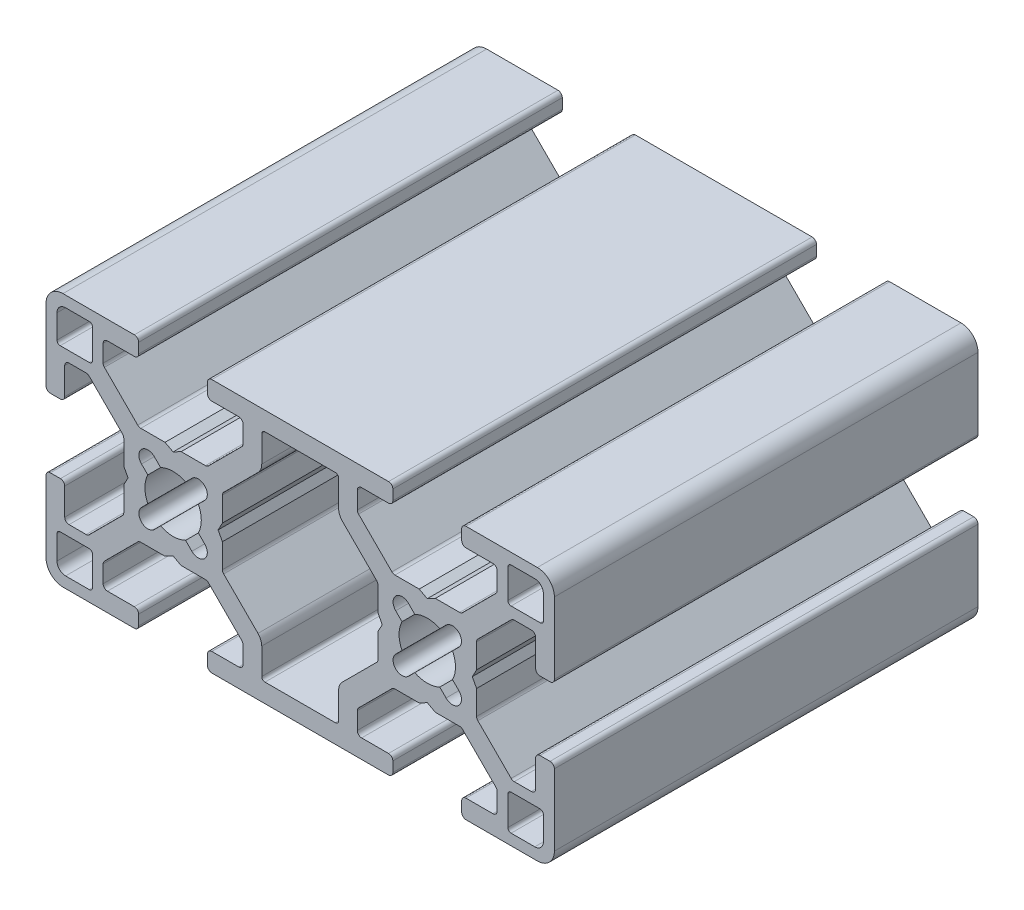
SolidWorks part; units mm, degrees
material "6105-T5 Aluminum"
ref_plane "Front Plane" through (0, 0, 0) normal (0, 0, 1) x (1, 0, 0)
ref_plane "Top Plane" through (0, 0, 0) normal (0, 1, 0) x (1, 0, 0)
ref_plane "Right Plane" through (0, 0, 0) normal (1, 0, 0) x (0, 0, -1)
sketch "Sketch1" plane through (0, 0, 0) normal (0, 0, 1) x (1, 0, 0)
  line L0 (12.7825, 3.7261) -> (13.5257, 2.983)
  line L1 (16.4743, 2.983) -> (17.2175, 3.7261)
  line L2 (18.7261, 2.2175) -> (17.983, 1.4743)
  line L3 (17.983, -1.4743) -> (18.7261, -2.2175)
  line L4 (17.2175, -3.7261) -> (16.4743, -2.983)
  line L5 (13.5257, -2.983) -> (12.7825, -3.7261)
  line L6 (11.2739, -2.2175) -> (12.017, -1.4743)
  line L7 (12.017, 1.4743) -> (11.2739, 2.2175)
  line L8 (-28.7046, 9.8946) -> (-28.7046, 12.6886)
  line L9 (-27.6886, 13.7046) -> (-24.8946, 13.7046)
  line L10 (-24.5136, 13.3236) -> (-24.5136, 9.8946)
  line L11 (-24.8946, 9.5136) -> (-28.3236, 9.5136)
  line L12 (-24.8946, -13.7046) -> (-27.6886, -13.7046)
  line L13 (-28.7046, -12.6886) -> (-28.7046, -9.8946)
  line L14 (-28.3236, -9.5136) -> (-24.8946, -9.5136)
  line L15 (-24.5136, -9.8946) -> (-24.5136, -13.3236)
  line L16 (4.9816, 8.2224) -> (9.0292, 4.1748)
  line L17 (9.178, 3.8155) -> (9.178, 0.9525)
  line L18 (9.178, 0.9525) -> (9.686, 0)
  line L19 (9.686, 0) -> (9.178, -0.9525)
  line L20 (9.178, -0.9525) -> (9.178, -3.8155)
  line L21 (9.0292, -4.1748) -> (4.9816, -8.2224)
  line L22 (4.5352, -9.3) -> (4.5352, -12.4092)
  line L23 (4.1542, -12.7902) -> (-4.1542, -12.7902)
  line L24 (-4.5352, -12.4092) -> (-4.5352, -9.3)
  line L25 (-4.9816, -8.2224) -> (-9.0292, -4.1748)
  line L26 (-9.178, -3.8155) -> (-9.178, -0.9525)
  line L27 (-9.178, -0.9525) -> (-9.686, 0)
  line L28 (-9.686, 0) -> (-9.178, 0.9525)
  line L29 (-9.178, 0.9525) -> (-9.178, 3.8155)
  line L30 (-9.0292, 4.1748) -> (-4.9816, 8.2224)
  line L31 (-4.5352, 9.3) -> (-4.5352, 12.4092)
  line L32 (-4.1542, 12.7902) -> (4.1542, 12.7902)
  line L33 (4.5352, 12.4092) -> (4.5352, 9.3)
  line L34 (-18.7261, -2.2175) -> (-17.983, -1.4743)
  line L35 (-17.983, 1.4743) -> (-18.7261, 2.2175)
  line L36 (-17.2175, 3.7261) -> (-16.4743, 2.983)
  line L37 (-13.5257, 2.983) -> (-12.7825, 3.7261)
  line L38 (-11.2739, 2.2175) -> (-12.017, 1.4743)
  line L39 (-12.017, -1.4743) -> (-11.2739, -2.2175)
  line L40 (-12.7825, -3.7261) -> (-13.5257, -2.983)
  line L41 (-16.4743, -2.983) -> (-17.2175, -3.7261)
  line L42 (24.8946, 13.7046) -> (27.6886, 13.7046)
  line L43 (28.7046, 12.6886) -> (28.7046, 9.8946)
  line L44 (28.3236, 9.5136) -> (24.8946, 9.5136)
  line L45 (24.5136, 9.8946) -> (24.5136, 13.3236)
  line L46 (24.5136, -13.3236) -> (24.5136, -9.8946)
  line L47 (24.8946, -9.5136) -> (28.3236, -9.5136)
  line L48 (28.7046, -9.8946) -> (28.7046, -12.6886)
  line L49 (27.6886, -13.7046) -> (24.8946, -13.7046)
  line L50 (-10.428, -15) -> (10.428, -15)
  line L51 (10.936, -14.492) -> (10.936, -13.2982)
  line L52 (10.428, -12.7902) -> (7.253, -12.7902)
  line L53 (6.745, -12.2822) -> (6.745, -10.2615)
  line L54 (6.8938, -9.9023) -> (10.8252, -5.9708)
  line L55 (11.1845, -5.822) -> (14.0475, -5.822)
  line L56 (14.0475, -5.822) -> (15, -5.314)
  line L57 (15, -5.314) -> (15.9525, -5.822)
  line L58 (15.9525, -5.822) -> (18.8155, -5.822)
  line L59 (19.1748, -5.9708) -> (23.1062, -9.9023)
  line L60 (23.255, -10.2615) -> (23.255, -12.2822)
  line L61 (22.747, -12.7902) -> (19.572, -12.7902)
  line L62 (19.064, -13.2982) -> (19.064, -14.492)
  line L63 (19.572, -15) -> (27.9934, -15)
  line L64 (30, -12.9934) -> (30, -4.572)
  line L65 (29.492, -4.064) -> (28.2982, -4.064)
  line L66 (27.7902, -4.572) -> (27.7902, -7.747)
  line L67 (27.2822, -8.255) -> (25.2615, -8.255)
  line L68 (24.9023, -8.1062) -> (20.9708, -4.1748)
  line L69 (20.822, -3.8155) -> (20.822, -0.9525)
  line L70 (20.822, -0.9525) -> (20.314, 0)
  line L71 (20.314, 0) -> (20.822, 0.9525)
  line L72 (20.822, 0.9525) -> (20.822, 3.8155)
  line L73 (20.9708, 4.1748) -> (24.9023, 8.1062)
  line L74 (25.2615, 8.255) -> (27.2822, 8.255)
  line L75 (27.7902, 7.747) -> (27.7902, 4.572)
  line L76 (28.2982, 4.064) -> (29.492, 4.064)
  line L77 (30, 4.572) -> (30, 12.9934)
  line L78 (27.9934, 15) -> (19.572, 15)
  line L79 (19.064, 14.492) -> (19.064, 13.2982)
  line L80 (19.572, 12.7902) -> (22.747, 12.7902)
  line L81 (23.255, 12.2822) -> (23.255, 10.2615)
  line L82 (23.1062, 9.9023) -> (19.1748, 5.9708)
  line L83 (18.8155, 5.822) -> (15.9525, 5.822)
  line L84 (15.9525, 5.822) -> (15, 5.314)
  line L85 (15, 5.314) -> (14.0475, 5.822)
  line L86 (14.0475, 5.822) -> (11.1845, 5.822)
  line L87 (10.8252, 5.9708) -> (6.8938, 9.9023)
  line L88 (6.745, 10.2615) -> (6.745, 12.2822)
  line L89 (7.253, 12.7902) -> (10.428, 12.7902)
  line L90 (10.936, 13.2982) -> (10.936, 14.492)
  line L91 (10.428, 15) -> (-10.428, 15)
  line L92 (-10.936, 14.492) -> (-10.936, 13.2982)
  line L93 (-10.428, 12.7902) -> (-7.253, 12.7902)
  line L94 (-6.745, 12.2822) -> (-6.745, 10.2615)
  line L95 (-6.8938, 9.9023) -> (-10.8252, 5.9708)
  line L96 (-11.1845, 5.822) -> (-14.0475, 5.822)
  line L97 (-14.0475, 5.822) -> (-15, 5.314)
  line L98 (-15, 5.314) -> (-15.9525, 5.822)
  line L99 (-15.9525, 5.822) -> (-18.8155, 5.822)
  line L100 (-19.1748, 5.9708) -> (-23.1062, 9.9023)
  line L101 (-23.255, 10.2615) -> (-23.255, 12.2822)
  line L102 (-22.747, 12.7902) -> (-19.572, 12.7902)
  line L103 (-19.064, 13.2982) -> (-19.064, 14.492)
  line L104 (-19.572, 15) -> (-27.9934, 15)
  line L105 (-30, 12.9934) -> (-30, 4.572)
  line L106 (-29.492, 4.064) -> (-28.2982, 4.064)
  line L107 (-27.7902, 4.572) -> (-27.7902, 7.747)
  line L108 (-27.2822, 8.255) -> (-25.2615, 8.255)
  line L109 (-24.9023, 8.1062) -> (-20.9708, 4.1748)
  line L110 (-20.822, 3.8155) -> (-20.822, 0.9525)
  line L111 (-20.822, 0.9525) -> (-20.314, 0)
  line L112 (-20.314, 0) -> (-20.822, -0.9525)
  line L113 (-20.822, -0.9525) -> (-20.822, -3.8155)
  line L114 (-20.9708, -4.1748) -> (-24.9023, -8.1062)
  line L115 (-25.2615, -8.255) -> (-27.2822, -8.255)
  line L116 (-27.7902, -7.747) -> (-27.7902, -4.572)
  line L117 (-28.2982, -4.064) -> (-29.492, -4.064)
  line L118 (-30, -4.572) -> (-30, -12.9934)
  line L119 (-27.9934, -15) -> (-19.572, -15)
  line L120 (-19.064, -14.492) -> (-19.064, -13.2982)
  line L121 (-19.572, -12.7902) -> (-22.747, -12.7902)
  line L122 (-23.255, -12.2822) -> (-23.255, -10.2615)
  line L123 (-23.1062, -9.9023) -> (-19.1748, -5.9708)
  line L124 (-18.8155, -5.822) -> (-15.9525, -5.822)
  line L125 (-15.9525, -5.822) -> (-15, -5.314)
  line L126 (-15, -5.314) -> (-14.0475, -5.822)
  line L127 (-14.0475, -5.822) -> (-11.1845, -5.822)
  line L128 (-10.8252, -5.9708) -> (-6.8938, -9.9023)
  line L129 (-6.745, -10.2615) -> (-6.745, -12.2822)
  line L130 (-7.253, -12.7902) -> (-10.428, -12.7902)
  line L131 (-10.936, -13.2982) -> (-10.936, -14.492)
  arc A0 (12.7825, 3.7261) -> (11.2739, 2.2175) centre (12.0282, 2.9718) ccw
  arc A1 (16.4743, 2.983) -> (13.5257, 2.983) centre (15, 0) ccw
  arc A2 (18.7261, 2.2175) -> (17.2175, 3.7261) centre (17.9718, 2.9718) ccw
  arc A3 (17.983, -1.4743) -> (17.983, 1.4743) centre (15, 0) ccw
  arc A4 (17.2175, -3.7261) -> (18.7261, -2.2175) centre (17.9718, -2.9718) ccw
  arc A5 (13.5257, -2.983) -> (16.4743, -2.983) centre (15, 0) ccw
  arc A6 (11.2739, -2.2175) -> (12.7825, -3.7261) centre (12.0282, -2.9718) ccw
  arc A7 (12.017, 1.4743) -> (12.017, -1.4743) centre (15, 0) ccw
  arc A8 (-28.7046, 9.8946) -> (-28.3236, 9.5136) centre (-28.3236, 9.8946) ccw
  arc A9 (-27.6886, 13.7046) -> (-28.7046, 12.6886) centre (-27.6886, 12.6886) ccw
  arc A10 (-24.5136, 13.3236) -> (-24.8946, 13.7046) centre (-24.8946, 13.3236) ccw
  arc A11 (-24.8946, 9.5136) -> (-24.5136, 9.8946) centre (-24.8946, 9.8946) ccw
  arc A12 (-24.8946, -13.7046) -> (-24.5136, -13.3236) centre (-24.8946, -13.3236) ccw
  arc A13 (-28.7046, -12.6886) -> (-27.6886, -13.7046) centre (-27.6886, -12.6886) ccw
  arc A14 (-28.3236, -9.5136) -> (-28.7046, -9.8946) centre (-28.3236, -9.8946) ccw
  arc A15 (-24.5136, -9.8946) -> (-24.8946, -9.5136) centre (-24.8946, -9.8946) ccw
  arc A16 (4.5352, 9.3) -> (4.9816, 8.2224) centre (6.0592, 9.3) ccw
  arc A17 (9.178, 3.8155) -> (9.0292, 4.1748) centre (8.67, 3.8155) ccw
  arc A18 (9.0292, -4.1748) -> (9.178, -3.8155) centre (8.67, -3.8155) ccw
  arc A19 (4.9816, -8.2224) -> (4.5352, -9.3) centre (6.0592, -9.3) ccw
  arc A20 (4.1542, -12.7902) -> (4.5352, -12.4092) centre (4.1542, -12.4092) ccw
  arc A21 (-4.5352, -12.4092) -> (-4.1542, -12.7902) centre (-4.1542, -12.4092) ccw
  arc A22 (-4.5352, -9.3) -> (-4.9816, -8.2224) centre (-6.0592, -9.3) ccw
  arc A23 (-9.178, -3.8155) -> (-9.0292, -4.1748) centre (-8.67, -3.8155) ccw
  arc A24 (-9.0292, 4.1748) -> (-9.178, 3.8155) centre (-8.67, 3.8155) ccw
  arc A25 (-4.9816, 8.2224) -> (-4.5352, 9.3) centre (-6.0592, 9.3) ccw
  arc A26 (-4.1542, 12.7902) -> (-4.5352, 12.4092) centre (-4.1542, 12.4092) ccw
  arc A27 (4.5352, 12.4092) -> (4.1542, 12.7902) centre (4.1542, 12.4092) ccw
  arc A28 (-18.7261, -2.2175) -> (-17.2175, -3.7261) centre (-17.9718, -2.9718) ccw
  arc A29 (-17.983, 1.4743) -> (-17.983, -1.4743) centre (-15, 0) ccw
  arc A30 (-17.2175, 3.7261) -> (-18.7261, 2.2175) centre (-17.9718, 2.9718) ccw
  arc A31 (-13.5257, 2.983) -> (-16.4743, 2.983) centre (-15, 0) ccw
  arc A32 (-11.2739, 2.2175) -> (-12.7825, 3.7261) centre (-12.0282, 2.9718) ccw
  arc A33 (-12.017, -1.4743) -> (-12.017, 1.4743) centre (-15, 0) ccw
  arc A34 (-12.7825, -3.7261) -> (-11.2739, -2.2175) centre (-12.0282, -2.9718) ccw
  arc A35 (-16.4743, -2.983) -> (-13.5257, -2.983) centre (-15, 0) ccw
  arc A36 (24.8946, 13.7046) -> (24.5136, 13.3236) centre (24.8946, 13.3236) ccw
  arc A37 (28.7046, 12.6886) -> (27.6886, 13.7046) centre (27.6886, 12.6886) ccw
  arc A38 (28.3236, 9.5136) -> (28.7046, 9.8946) centre (28.3236, 9.8946) ccw
  arc A39 (24.5136, 9.8946) -> (24.8946, 9.5136) centre (24.8946, 9.8946) ccw
  arc A40 (24.5136, -13.3236) -> (24.8946, -13.7046) centre (24.8946, -13.3236) ccw
  arc A41 (24.8946, -9.5136) -> (24.5136, -9.8946) centre (24.8946, -9.8946) ccw
  arc A42 (28.7046, -9.8946) -> (28.3236, -9.5136) centre (28.3236, -9.8946) ccw
  arc A43 (27.6886, -13.7046) -> (28.7046, -12.6886) centre (27.6886, -12.6886) ccw
  arc A44 (10.428, -15) -> (10.936, -14.492) centre (10.428, -14.492) ccw
  arc A45 (10.936, -13.2982) -> (10.428, -12.7902) centre (10.428, -13.2982) ccw
  arc A46 (6.745, -12.2822) -> (7.253, -12.7902) centre (7.253, -12.2822) ccw
  arc A47 (6.8938, -9.9023) -> (6.745, -10.2615) centre (7.253, -10.2615) ccw
  arc A48 (11.1845, -5.822) -> (10.8252, -5.9708) centre (11.1845, -6.33) ccw
  arc A49 (19.1748, -5.9708) -> (18.8155, -5.822) centre (18.8155, -6.33) ccw
  arc A50 (23.255, -10.2615) -> (23.1062, -9.9023) centre (22.747, -10.2615) ccw
  arc A51 (22.747, -12.7902) -> (23.255, -12.2822) centre (22.747, -12.2822) ccw
  arc A52 (19.572, -12.7902) -> (19.064, -13.2982) centre (19.572, -13.2982) ccw
  arc A53 (19.064, -14.492) -> (19.572, -15) centre (19.572, -14.492) ccw
  arc A54 (27.9934, -15) -> (30, -12.9934) centre (27.9934, -12.9934) ccw
  arc A55 (30, -4.572) -> (29.492, -4.064) centre (29.492, -4.572) ccw
  arc A56 (28.2982, -4.064) -> (27.7902, -4.572) centre (28.2982, -4.572) ccw
  arc A57 (27.2822, -8.255) -> (27.7902, -7.747) centre (27.2822, -7.747) ccw
  arc A58 (24.9023, -8.1062) -> (25.2615, -8.255) centre (25.2615, -7.747) ccw
  arc A59 (20.822, -3.8155) -> (20.9708, -4.1748) centre (21.33, -3.8155) ccw
  arc A60 (20.9708, 4.1748) -> (20.822, 3.8155) centre (21.33, 3.8155) ccw
  arc A61 (25.2615, 8.255) -> (24.9023, 8.1062) centre (25.2615, 7.747) ccw
  arc A62 (27.7902, 7.747) -> (27.2822, 8.255) centre (27.2822, 7.747) ccw
  arc A63 (27.7902, 4.572) -> (28.2982, 4.064) centre (28.2982, 4.572) ccw
  arc A64 (29.492, 4.064) -> (30, 4.572) centre (29.492, 4.572) ccw
  arc A65 (30, 12.9934) -> (27.9934, 15) centre (27.9934, 12.9934) ccw
  arc A66 (19.572, 15) -> (19.064, 14.492) centre (19.572, 14.492) ccw
  arc A67 (19.064, 13.2982) -> (19.572, 12.7902) centre (19.572, 13.2982) ccw
  arc A68 (23.255, 12.2822) -> (22.747, 12.7902) centre (22.747, 12.2822) ccw
  arc A69 (23.1062, 9.9023) -> (23.255, 10.2615) centre (22.747, 10.2615) ccw
  arc A70 (18.8155, 5.822) -> (19.1748, 5.9708) centre (18.8155, 6.33) ccw
  arc A71 (10.8252, 5.9708) -> (11.1845, 5.822) centre (11.1845, 6.33) ccw
  arc A72 (6.745, 10.2615) -> (6.8938, 9.9023) centre (7.253, 10.2615) ccw
  arc A73 (7.253, 12.7902) -> (6.745, 12.2822) centre (7.253, 12.2822) ccw
  arc A74 (10.428, 12.7902) -> (10.936, 13.2982) centre (10.428, 13.2982) ccw
  arc A75 (10.936, 14.492) -> (10.428, 15) centre (10.428, 14.492) ccw
  arc A76 (-10.428, 15) -> (-10.936, 14.492) centre (-10.428, 14.492) ccw
  arc A77 (-10.936, 13.2982) -> (-10.428, 12.7902) centre (-10.428, 13.2982) ccw
  arc A78 (-6.745, 12.2822) -> (-7.253, 12.7902) centre (-7.253, 12.2822) ccw
  arc A79 (-6.8938, 9.9023) -> (-6.745, 10.2615) centre (-7.253, 10.2615) ccw
  arc A80 (-11.1845, 5.822) -> (-10.8252, 5.9708) centre (-11.1845, 6.33) ccw
  arc A81 (-19.1748, 5.9708) -> (-18.8155, 5.822) centre (-18.8155, 6.33) ccw
  arc A82 (-23.255, 10.2615) -> (-23.1062, 9.9023) centre (-22.747, 10.2615) ccw
  arc A83 (-22.747, 12.7902) -> (-23.255, 12.2822) centre (-22.747, 12.2822) ccw
  arc A84 (-19.572, 12.7902) -> (-19.064, 13.2982) centre (-19.572, 13.2982) ccw
  arc A85 (-19.064, 14.492) -> (-19.572, 15) centre (-19.572, 14.492) ccw
  arc A86 (-27.9934, 15) -> (-30, 12.9934) centre (-27.9934, 12.9934) ccw
  arc A87 (-30, 4.572) -> (-29.492, 4.064) centre (-29.492, 4.572) ccw
  arc A88 (-28.2982, 4.064) -> (-27.7902, 4.572) centre (-28.2982, 4.572) ccw
  arc A89 (-27.2822, 8.255) -> (-27.7902, 7.747) centre (-27.2822, 7.747) ccw
  arc A90 (-24.9023, 8.1062) -> (-25.2615, 8.255) centre (-25.2615, 7.747) ccw
  arc A91 (-20.822, 3.8155) -> (-20.9708, 4.1748) centre (-21.33, 3.8155) ccw
  arc A92 (-20.9708, -4.1748) -> (-20.822, -3.8155) centre (-21.33, -3.8155) ccw
  arc A93 (-25.2615, -8.255) -> (-24.9023, -8.1062) centre (-25.2615, -7.747) ccw
  arc A94 (-27.7902, -7.747) -> (-27.2822, -8.255) centre (-27.2822, -7.747) ccw
  arc A95 (-27.7902, -4.572) -> (-28.2982, -4.064) centre (-28.2982, -4.572) ccw
  arc A96 (-29.492, -4.064) -> (-30, -4.572) centre (-29.492, -4.572) ccw
  arc A97 (-30, -12.9934) -> (-27.9934, -15) centre (-27.9934, -12.9934) ccw
  arc A98 (-19.572, -15) -> (-19.064, -14.492) centre (-19.572, -14.492) ccw
  arc A99 (-19.064, -13.2982) -> (-19.572, -12.7902) centre (-19.572, -13.2982) ccw
  arc A100 (-23.255, -12.2822) -> (-22.747, -12.7902) centre (-22.747, -12.2822) ccw
  arc A101 (-23.1062, -9.9023) -> (-23.255, -10.2615) centre (-22.747, -10.2615) ccw
  arc A102 (-18.8155, -5.822) -> (-19.1748, -5.9708) centre (-18.8155, -6.33) ccw
  arc A103 (-10.8252, -5.9708) -> (-11.1845, -5.822) centre (-11.1845, -6.33) ccw
  arc A104 (-6.745, -10.2615) -> (-6.8938, -9.9023) centre (-7.253, -10.2615) ccw
  arc A105 (-7.253, -12.7902) -> (-6.745, -12.2822) centre (-7.253, -12.2822) ccw
  arc A106 (-10.428, -12.7902) -> (-10.936, -13.2982) centre (-10.428, -13.2982) ccw
  arc A107 (-10.936, -14.492) -> (-10.428, -15) centre (-10.428, -14.492) ccw
extrude "Extrude1" add sketch "Sketch1" against normal blind 50
